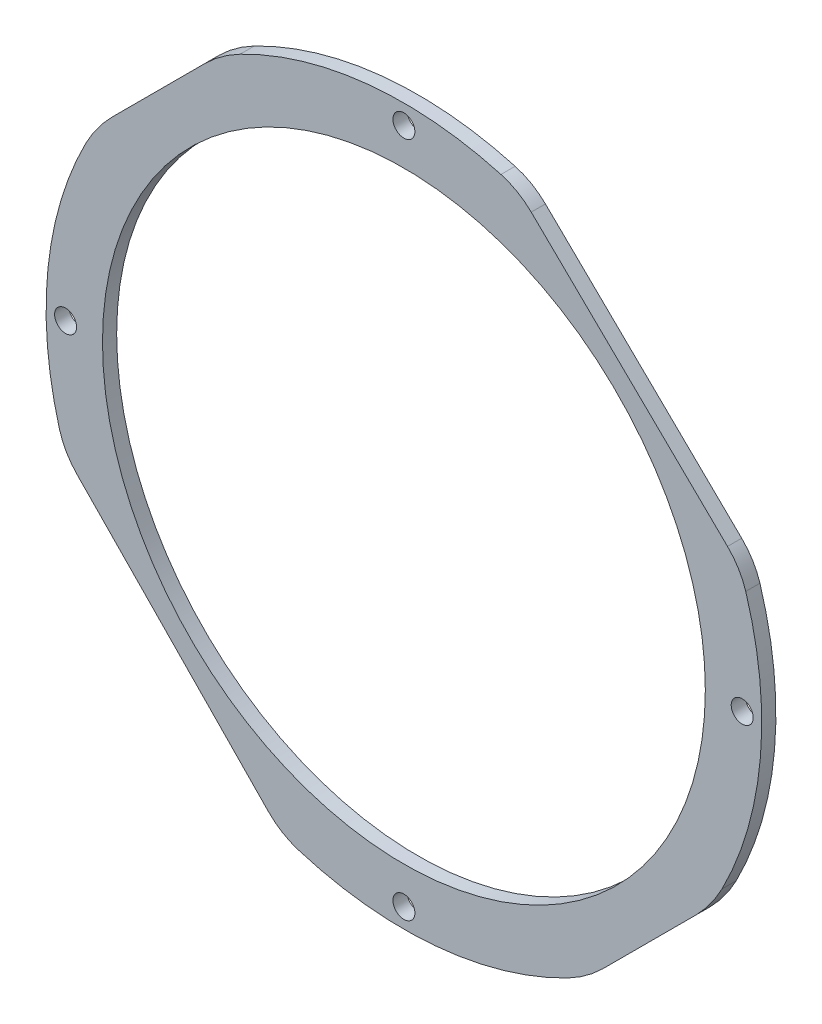
SolidWorks part; units mm, degrees
material "Thornel Mat VMA"
ref_plane "前视基准面" through (0, 0, 0) normal (0, 0, 1) x (1, 0, 0)
ref_plane "上视基准面" through (0, 0, 0) normal (0, 1, 0) x (1, 0, 0)
ref_plane "右视基准面" through (0, 0, 0) normal (1, 0, 0) x (0, 0, -1)
sketch "草图1" plane through (0, 0, 0) normal (0, 0, 1) x (1, 0, 0)
  line L0 (0, 0) -> (0, 47.7) construction
  circle A0 centre (0, 0) radius 47.7 construction
  circle A1 centre (0, 47.7) radius 1.55
  circle A2 centre (47.7, 0) radius 1.55
  circle A3 centre (0, -47.7) radius 1.55
  circle A4 centre (-47.7, 0) radius 1.55
  circle A5 centre (0, 0) radius 42.5
  circle A6 centre (0, 0) radius 50.45
  point P13 (0, 0)
  dimension "D1" = 95.4
  dimension "D2" = 3.1
  dimension "D4" = 85
  dimension "D5" = 100.9
  dimension "D3" = 4
extrude "凸台-拉伸1" add sketch "草图1" along normal blind 2
sketch "草图2" plane through (0, 0, 2) normal (0, 0, 1) x (1, 0, 0)
  line L0 (0, 0) -> (0, 47.7) construction
  line L1 (0, 0) -> (-35.6735, 35.6735) construction
  line L2 (-26.157, 43.1395) -> (-43.1395, 26.157)
  line L6 (43.1395, 26.157) -> (26.157, 43.1395)
  line L7 (26.157, -43.1395) -> (43.1395, -26.157)
  line L8 (-43.1395, -26.157) -> (-26.157, -43.1395)
  circle A1 centre (0, 0) radius 50.45 construction
  arc A2 (-26.157, 43.1395) -> (-43.1395, 26.157) centre (0, 0) ccw
  arc A3 (43.1395, 26.157) -> (26.157, 43.1395) centre (0, 0) ccw
  arc A4 (26.157, -43.1395) -> (43.1395, -26.157) centre (0, 0) ccw
  arc A5 (-43.1395, -26.157) -> (-26.157, -43.1395) centre (0, 0) ccw
  point P12 (-46.0188, 46.0188)
  point P13 (-34.2817, 34.2817)
  point P20 (0, 0)
  dimension "D1" = 45
  dimension "D3" = 98
  dimension "D2" = 4
extrude "切除-拉伸1" cut sketch "草图2" against normal blind 8
fillet "圆角1" radius 20 8 edges at (-26.157, -43.1395, 1) (-43.1395, -26.157, 1) (-43.1395, 26.157, 1) (-26.157, 43.1395, 1) (26.157, 43.1395, 1) (43.1395, 26.157, 1) (43.1395, -26.157, 1) (26.157, -43.1395, 1)
sketch "草图3" plane through (0, 0, 2) normal (0, 0, 1) x (1, 0, 0)
  line L0 (-28.0831, -41.2134) -> (-41.2134, -28.0831) construction
  line L1 (-29.0985, -40.3951) -> (-44.5471, -40.3951)
  line L2 (-29.0985, -40.3951) -> (-29.0985, -24.5522)
  line L3 (-29.0985, -24.5522) -> (-44.5471, -24.5522)
  line L4 (-44.5471, -40.3951) -> (-44.5471, -24.5522)
  line L5 (-29.0985, -40.3951) -> (-44.5471, -24.5522) construction
  line L6 (-29.0985, -24.5522) -> (-44.5471, -40.3951) construction
  point P0 (-36.8228, -32.4737)
sketch "草图4" plane through (0, 0, 2) normal (0, 0, 1) x (1, 0, 0)
  line L0 (-29.0985, -40.3951) -> (-44.5471, -24.5522) construction
  line L1 (-18.7042, -51.0548) -> (-51.9867, -16.9227)
  line L2 (-51.9867, -16.9227) -> (-49.4808, -14.4792)
  line L3 (-49.4808, -14.4792) -> (-16.1983, -48.6114)
  line L4 (-16.1983, -48.6114) -> (-18.7042, -51.0548)
  line L5 (0, 0) -> (-30.052, 30.052) construction
  line L6 (0, 0) -> (0, 49.25) construction
  line L7 (48.6114, 16.1983) -> (51.0548, 18.7042)
  line L8 (14.4792, 49.4808) -> (48.6114, 16.1983)
  line L9 (16.9227, 51.9867) -> (14.4792, 49.4808)
  line L10 (51.0548, 18.7042) -> (16.9227, 51.9867)
  circle A0 centre (0, 0) radius 42.5 construction
  circle A1 centre (0, 47.7) radius 1.55 construction
  dimension "D1" = 3.5
  dimension "D2" = 45
extrude "切除-拉伸2" cut sketch "草图4" against normal blind 10
sketch "草图5" plane through (0, 0, 2) normal (0, 0, 1) x (1, 0, 0)
  line L2 (-36.8228, -32.4737) -> (-42.5797, -26.5698)
  line L3 (-41.2134, -28.0831) -> (-36.8228, -32.4737)
  line L4 (-36.8228, -32.4737) -> (-42.5797, -26.5698)
  line L5 (-41.2134, -28.0831) -> (-36.8228, -32.4737)
  line L6 (26.5698, 42.5797) -> (32.4737, 36.8228)
  line L7 (32.4737, 36.8228) -> (28.0831, 41.2134)
  line L8 (26.5698, 42.5797) -> (32.4737, 36.8228)
  line L9 (32.4737, 36.8228) -> (28.0831, 41.2134)
  arc A1 (-42.5797, -26.5698) -> (-41.2134, -28.0831) centre (-27.0713, -13.9409) ccw
  arc A2 (-42.5797, -26.5698) -> (-41.2134, -28.0831) centre (-27.0713, -13.9409) ccw
  arc A3 (28.0831, 41.2134) -> (26.5698, 42.5797) centre (13.9409, 27.0713) ccw
  arc A4 (28.0831, 41.2134) -> (26.5698, 42.5797) centre (13.9409, 27.0713) ccw
  dimension "D1" = 0
  dimension "D2" = 0
extrude "切除-拉伸3" cut sketch "草图5" against normal blind 10
fillet "圆角2" radius 10 4 edges at (-47.7651, -16.2387, 1) (-17.4373, -47.3407, 1) (16.2387, 47.7651, 1) (47.3407, 17.4373, 1)
